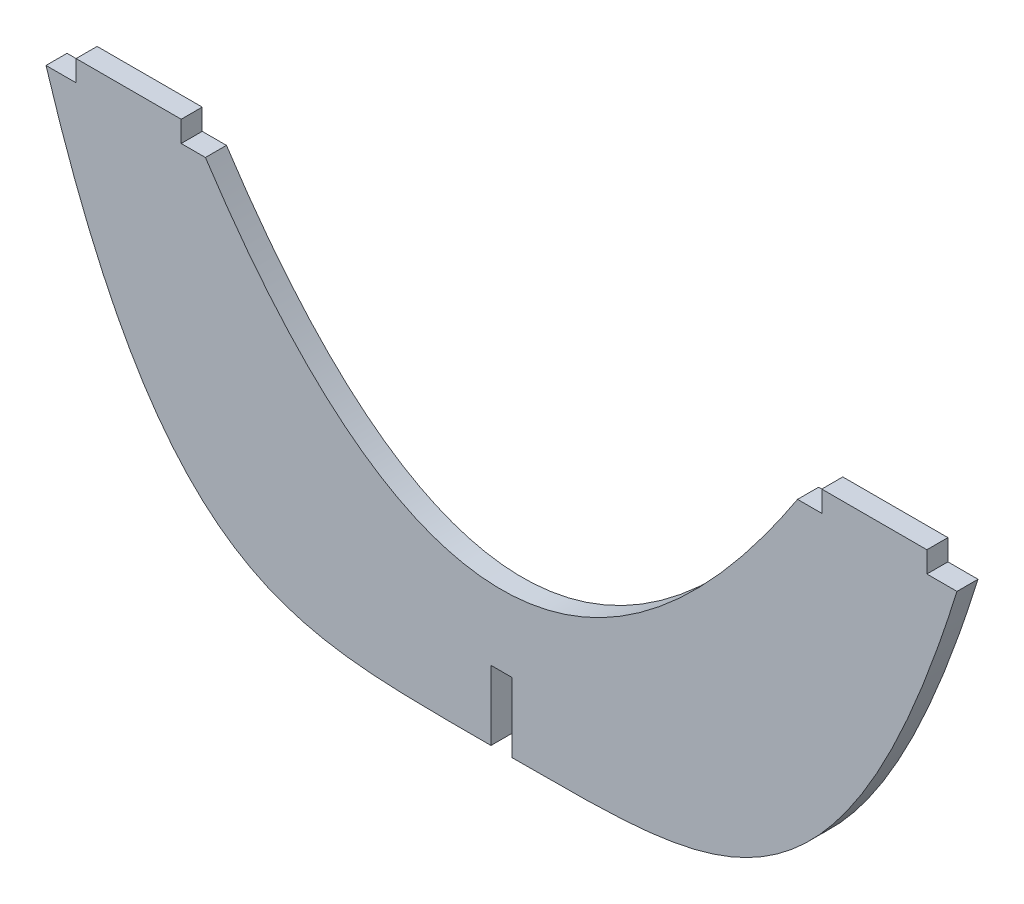
SolidWorks part; units mm, degrees
other "标注1"
sketch "草图3" plane through (-62.7505, 55.2968, 3) normal (-0.0241, 0.0376, 0.999) x (0.9938, -0.1078, 0.028)
ref_plane "前视基准面" through (0, 0, 0) normal (0, 0, 1) x (1, 0, 0)
ref_plane "上视基准面" through (0, 0, 0) normal (0, 1, 0) x (1, 0, 0)
ref_plane "右视基准面" through (0, 0, 0) normal (1, 0, 0) x (0, 0, -1)
other "Configuration Table"
sketch "草图1" plane through (0, 0, 0) normal (0, 0, 1) x (1, 0, 0)
  line L8 (0, 0) -> (0, 135) construction
  line L41 (-65, 52.2968) -> (-60.7052, 52.2968)
  line L42 (-60.7052, 52.2968) -> (-60.7052, 55.2968)
  line L43 (-60.7052, 55.2968) -> (-45.7052, 55.2968)
  line L44 (-45.7052, 55.2968) -> (-45.7052, 52.2968)
  line L45 (-45.7052, 52.2968) -> (-42.2495, 52.2968)
  line L46 (65, 52.2968) -> (60.7052, 52.2968)
  line L47 (60.7052, 52.2968) -> (60.7052, 55.2968)
  line L48 (60.7052, 55.2968) -> (45.7052, 55.2968)
  line L49 (45.7052, 55.2968) -> (45.7052, 52.2968)
  line L50 (45.7052, 52.2968) -> (42.2495, 52.2968)
  line L51 (0, 10.2) -> (-1.5, 10.2)
  line L52 (-1.5, 10.2) -> (-1.5, 0)
  line L53 (0, 10.2) -> (1.5, 10.2)
  line L54 (1.5, 10.2) -> (1.5, 0)
  spline S0 degree 4 poles (-69.9948, 70.3211) (-34.9974, -70.3211) (0, 70.3211) (34.9974, -70.3211) (69.9948, 70.3211) knots 0 0 0 0 0 1 1 1 1 1 construction
  spline S1 degree 4 poles (-65, 52.2968) (-32.5, -52.2968) (0, 52.2968) (32.5, -52.2968) (65, 52.2968) knots 0.03568 0.03568 0.03568 0.03568 0.03568 0.96432 0.96432 0.96432 0.96432 0.96432
  spline S2 degree 2 poles (-42.2495, 52.2968) (0, -12.2968) (42.2495, 52.2968) knots 0 0 0 1 1 1
  point P5 (0, 0)
  point P23 (0, 0)
  point P25 (0, 0)
  point P26 (0, 0)
  point P27 (0, 0)
  point P28 (0, 0)
  point P29 (0, 0)
  point P30 (0, 0)
  point P31 (0, 0)
  point P32 (0, 0)
  point P33 (0, 0)
  dimension "D1" = 10.2
  dimension "D2" = 1.5
  dimension "D3" = 3
  dimension "D4" = 15
  dimension "D5" = 15
extrude "凸台-拉伸1" add sketch "草图1" along normal blind 3
sketch "草图4" plane through (0, 0, 3) normal (0, 0, 1) x (1, 0, 0)
  line L0 (0, 16.2648) -> (0, -9.2812) construction
  line L1 (-1.5, 0) -> (-1.5, -2.6861)
  line L3 (-1.5, 0) -> (-1.5, 10.2)
  line L4 (-1.5, 10.2) -> (1.5, 10.2)
  line L5 (1.5, 0.0005) -> (1.5, 10.2)
  line L6 (-1.5, -2.6861) -> (1.5, -2.6861)
  line L7 (1.5, -2.6861) -> (1.5, 0.0005)
  spline S0 degree 4 poles (-65, 52.2968) (-32.5, -52.2968) (0, 52.2968) (32.5, -52.2968) (65, 52.2968) knots 0.03568 0.03568 0.03568 0.03568 0.03568 0.96432 0.96432 0.96432 0.96432 0.96432 construction
  dimension "D1" = 3
  dimension "D2" = 1.5
  dimension "D3" = 10.2
extrude "切除-拉伸4" cut sketch "草图4" against normal blind 10
sketch "草图6" plane through (0, 0, 0) normal (0, 0, -1) x (-1, 0, 0)
  line L0 (-1.5, 0) -> (-1.5, 10.2) construction
  line L1 (1.5, 10.2) -> (-1.5, 10.2)
  line L2 (1.5, 10.2) -> (1.5, 9.91)
  line L3 (1.5, 9.91) -> (-1.5, 9.91)
  line L4 (-1.5, 10.2) -> (-1.5, 9.91)
  dimension "D1" = 0.29
extrude "凸台-拉伸4" add sketch "草图6" against normal blind 3
